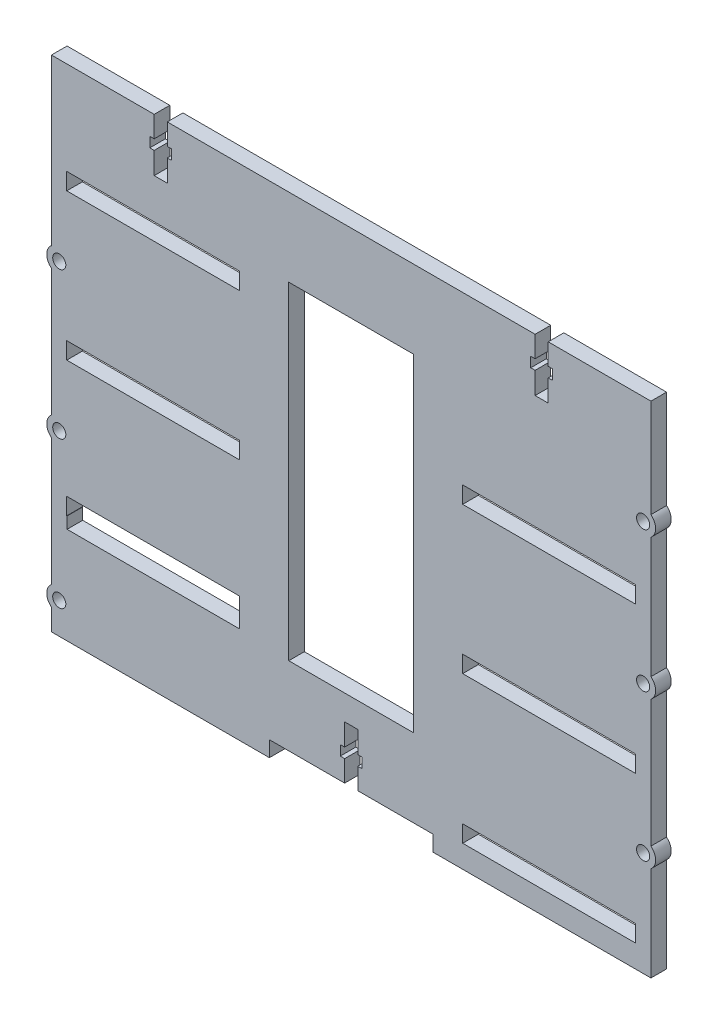
SolidWorks part; units mm, degrees
ref_plane "Front Plane" through (0, 0, 0) normal (0, 0, 1) x (1, 0, 0)
ref_plane "Top Plane" through (0, 0, 0) normal (0, 1, 0) x (1, 0, 0)
ref_plane "Right Plane" through (0, 0, 0) normal (1, 0, 0) x (0, 0, -1)
sketch "Sketch1" plane through (0, 0, 0) normal (0, 0, 1) x (1, 0, 0)
  line L0 (-192, 100.8775) -> (-192, 60.1225)
  line L1 (-192, 160) -> (-159.1, 160)
  line L2 (-192, 160) -> (-192, 107.1225)
  line L3 (-192, 0) -> (-122, 0)
  line L4 (0, 160) -> (0, 128.5225)
  line L5 (-187, 130) -> (-131.8, 130)
  line L6 (-187, 130) -> (-187, 124.95)
  line L7 (-187, 124.95) -> (-131.8, 124.95)
  line L8 (-131.8, 130) -> (-131.8, 124.95)
  line L9 (-192, 53.8775) -> (-192, 13.1225)
  line L10 (-187, 83) -> (-131.8, 83)
  line L11 (-187, 83) -> (-187, 77.95)
  line L12 (-187, 77.95) -> (-131.8, 77.95)
  line L13 (-131.8, 83) -> (-131.8, 77.95)
  line L14 (-192, 6.8775) -> (-192, 0)
  line L15 (-187, 36) -> (-131.8, 36)
  line L16 (-187, 36) -> (-187, 30.95)
  line L17 (-187, 30.95) -> (-131.8, 30.95)
  line L18 (-131.8, 36) -> (-131.8, 30.95)
  line L19 (0, 122.2775) -> (0, 83.5725)
  line L20 (0, 77.3275) -> (0, 36.5725)
  line L21 (-5, 101.4) -> (-60.2, 101.4)
  line L22 (-5, 101.4) -> (-5, 106.45)
  line L23 (-5, 106.45) -> (-60.2, 106.45)
  line L24 (-60.2, 101.4) -> (-60.2, 106.45)
  line L25 (0, 30.3275) -> (0, 0)
  line L26 (-5, 54.4) -> (-60.2, 54.4)
  line L27 (-5, 54.4) -> (-5, 59.45)
  line L28 (-5, 59.45) -> (-60.2, 59.45)
  line L29 (-60.2, 54.4) -> (-60.2, 59.45)
  line L30 (-159.1, 160) -> (-159.1, 153.2)
  line L31 (-5, 7.4) -> (-60.2, 7.4)
  line L32 (-5, 7.4) -> (-5, 12.45)
  line L33 (-5, 12.45) -> (-60.2, 12.45)
  line L34 (-60.2, 7.4) -> (-60.2, 12.45)
  line L35 (-159.1, 153.2) -> (-160.5, 153.2)
  line L36 (-160.5, 153.2) -> (-160.5, 150)
  line L37 (-160.5, 150) -> (-159.1, 150)
  line L38 (-159.1, 150) -> (-159.1, 143)
  line L39 (-159.1, 143) -> (-154.9, 143)
  line L40 (-154.9, 143) -> (-154.9, 150)
  line L41 (-154.9, 150) -> (-153.5, 150)
  line L42 (-153.5, 150) -> (-153.5, 153.2)
  line L43 (-153.5, 153.2) -> (-154.9, 153.2)
  line L44 (-154.9, 153.2) -> (-154.9, 160)
  line L45 (-32.9, 153.2) -> (-32.9, 160)
  line L46 (-31.5, 153.2) -> (-32.9, 153.2)
  line L47 (-31.5, 150) -> (-31.5, 153.2)
  line L48 (-32.9, 150) -> (-31.5, 150)
  line L49 (-32.9, 143) -> (-32.9, 150)
  line L50 (-37.1, 143) -> (-32.9, 143)
  line L51 (-37.1, 150) -> (-37.1, 143)
  line L52 (-38.5, 150) -> (-37.1, 150)
  line L53 (-38.5, 153.2) -> (-38.5, 150)
  line L54 (-37.1, 153.2) -> (-38.5, 153.2)
  line L55 (-37.1, 160) -> (-37.1, 153.2)
  line L58 (-192, 80) -> (0, 80) construction
  line L83 (-70, 0) -> (0, 0)
  line L85 (-122, 0) -> (-122, 5)
  line L86 (-122, 5) -> (-98.1, 5)
  line L87 (-70, 0) -> (-70, 5)
  line L88 (-32.9, 160) -> (0, 160)
  line L89 (-154.9, 160) -> (-37.1, 160)
  line L90 (-96, 5) -> (-96, 30.3525) construction
  line L91 (-93.9, 22) -> (-98.1, 22)
  line L92 (-98.1, 22) -> (-98.1, 15)
  line L93 (-98.1, 15) -> (-99.5, 15)
  line L94 (-99.5, 11.8) -> (-98.1, 11.8)
  line L95 (-98.1, 11.8) -> (-98.1, 5)
  line L96 (-99.5, 15) -> (-99.5, 11.8)
  line L98 (-92.5, 15) -> (-92.5, 11.8)
  line L99 (-93.9, 11.8) -> (-93.9, 5)
  line L100 (-92.5, 11.8) -> (-93.9, 11.8)
  line L101 (-93.9, 15) -> (-92.5, 15)
  line L102 (-93.9, 22) -> (-93.9, 15)
  line L103 (-93.9, 5) -> (-70, 5)
  circle A0 centre (-189.5, 104) radius 2.1
  arc A1 (-192, 107.1225) -> (-192, 100.8775) centre (-189.5, 104) ccw
  circle A2 centre (-189.5, 57) radius 2.1
  arc A3 (-192, 60.1225) -> (-192, 53.8775) centre (-189.5, 57) ccw
  circle A4 centre (-189.5, 10) radius 2.1
  arc A5 (-192, 13.1225) -> (-192, 6.8775) centre (-189.5, 10) ccw
  circle A6 centre (-2.5, 125.4) radius 2.1
  arc A7 (0, 122.2775) -> (0, 128.5225) centre (-2.5, 125.4) ccw
  circle A8 centre (-2.5, 80.45) radius 2.1
  arc A9 (0, 77.3275) -> (0, 83.5725) centre (-2.5, 80.45) ccw
  circle A10 centre (-2.5, 33.45) radius 2.1
  arc A11 (0, 30.3275) -> (0, 36.5725) centre (-2.5, 33.45) ccw
  point P68 (-157, 143)
  point P81 (-70, 2.5)
  point P82 (-35, 143)
  point P98 (-96, 22)
  dimension "D6" = 4.2
  dimension "D7" = 20.95
  dimension "D8" = 2.5
  dimension "D9" = 5.05
  dimension "D13" = 4
  dimension "D14" = 4.2
  dimension "D15" = 2.5
  dimension "D17" = 4
  dimension "D21" = 4.2
  dimension "D22" = 2.5
  dimension "D24" = 4
  dimension "D25" = 4.2
  dimension "D26" = 2.5
  dimension "D27" = 5.05
  dimension "D31" = 4.2
  dimension "D32" = 2.5
  dimension "D33" = 20.95
  dimension "D34" = 5.05
  dimension "D35" = 21
  dimension "D36" = 4.2
  dimension "D37" = 2.5
  dimension "D38" = 20.95
  dimension "D39" = 4
  dimension "D40" = 21
  dimension "D42" = 4
  dimension "D43" = 4
  dimension "D65" = 34.6
  dimension "D1" = 192
  dimension "D2" = 160
  dimension "D3" = 55.2
  dimension "D4" = 5
  dimension "D5" = 30
  dimension "D10" = 5.05
  dimension "D11" = 21
  dimension "D12" = 5
  dimension "D16" = 20.95
  dimension "D18" = 5.05
  dimension "D19" = 21
  dimension "D20" = 5
  dimension "D23" = 20.95
  dimension "D28" = 18.5
  dimension "D29" = 5
  dimension "D30" = 55.2
  dimension "D41" = 5.05
  dimension "D44" = 7
  dimension "D45" = 4.2
  dimension "D46" = 4.2
  dimension "D47" = 6.8
  dimension "D48" = 3.2
  dimension "D49" = 17
  dimension "D50" = 1.4
  dimension "D51" = 3.2
  dimension "D52" = 35
  dimension "D54" = 5
  dimension "D55" = 70
  dimension "D56" = 70
  dimension "D57" = 35
  dimension "D58" = 122
  dimension "D59" = 2.1
  dimension "D60" = 3.5
  dimension "D61" = 17
  dimension "D62" = 6.8
  dimension "D63" = 3.2
  dimension "D64" = 26
  dimension "D53" = 2
extrude "Boss-Extrude1" add sketch "Sketch1" along normal blind 5
sketch "Sketch2" plane through (0, 0, 5) normal (0, 0, 1) x (1, 0, 0)
  line L0 (-187, 130) -> (-187, 124.95) construction
  line L1 (-187.1, 130.175) -> (-131.7, 130.175)
  line L2 (-187.1, 130.175) -> (-187.1, 124.775)
  line L3 (-187.1, 124.775) -> (-131.7, 124.775)
  line L4 (-131.7, 130.175) -> (-131.7, 124.775)
  line L5 (-131.7, 124.775) -> (-60.2, 124.775) construction
  line L7 (-187.4, 104) -> (-163.5896, 104) construction
  line L8 (-188.6868, 58.9362) -> (-172.7381, 58.9362) construction
  line L9 (-60.3, 106.625) -> (-4.9, 106.625)
  line L10 (-131.7, 77.825) -> (-131.7, 83.225)
  line L11 (-187.1, 83.225) -> (-131.7, 83.225)
  line L12 (-187.1, 77.825) -> (-187.1, 83.225)
  line L13 (-187.1, 77.825) -> (-131.7, 77.825)
  line L14 (-187.1, 40.0473) -> (-131.7, 40.0473)
  line L15 (-187.1, 40.0473) -> (-187.1, 34.6473)
  line L16 (-187.1, 34.6473) -> (-131.7, 34.6473)
  line L17 (-131.7, 40.0473) -> (-131.7, 34.6473)
  line L18 (-60.3, 106.625) -> (-60.3, 101.225)
  line L28 (-60.3, 101.225) -> (-4.9, 101.225)
  line L29 (-4.9, 106.625) -> (-4.9, 101.225)
  line L30 (-60.2, 106.45) -> (-60.2, 101.4) construction
  line L31 (-2.5, 80.45) -> (-40.0415, 80.45) construction
  line L32 (-4.9, 54.275) -> (-4.9, 59.675)
  line L33 (-60.3, 59.675) -> (-4.9, 59.675)
  line L34 (-60.3, 54.275) -> (-60.3, 59.675)
  line L35 (-60.3, 54.275) -> (-4.9, 54.275)
  line L36 (-2.5, 33.45) -> (-34.1533, 33.45) construction
  line L37 (-60.3, 12.625) -> (-4.9, 12.625)
  line L38 (-60.3, 12.625) -> (-60.3, 7.225)
  line L39 (-60.3, 7.225) -> (-4.9, 7.225)
  line L40 (-4.9, 12.625) -> (-4.9, 7.225)
  circle A0 centre (-189.5, 104) radius 2.1 construction
  circle A1 centre (-189.5, 57) radius 2.1 construction
  point P6 (-187, 127.475)
  point P30 (-60.2, 103.925)
  dimension "D5" = 55.4
  dimension "D1" = 55.4
  dimension "D2" = 0.1
  dimension "D3" = 5.4
  dimension "D4" = 2.7
  dimension "D6" = 0.1
  dimension "D7" = 5.4
  dimension "D8" = 2.7
extrude "Cut-Extrude1" cut sketch "Sketch2" against normal blind 10
sketch "Sketch3" plane through (0, 0, 5) normal (0, 0, 1) x (1, 0, 0)
  line L0 (-192, 0) -> (-122, 0) construction
  line L1 (-122.2, 0) -> (-69.8, 0)
  line L2 (-122.2, 0) -> (-122.2, 5)
  line L3 (-122.2, 5) -> (-69.8, 5)
  line L4 (-69.8, 0) -> (-69.8, 5)
  line L6 (-122, 0) -> (-122, 5) construction
  dimension "D1" = 5
  dimension "D2" = 52.4
  dimension "D3" = 0.2
extrude "Cut-Extrude2" cut sketch "Sketch3" against normal blind 10
sketch "Sketch4" plane through (0, 0, 5) normal (0, 0, 1) x (1, 0, 0)
  line L0 (-37.1, 160) -> (-154.9, 160) construction
  line L1 (-116, 135) -> (-76, 135)
  line L2 (-116, 135) -> (-116, 30)
  line L3 (-116, 30) -> (-76, 30)
  line L4 (-76, 135) -> (-76, 30)
  line L5 (-122.2, 5) -> (-98.1, 5) construction
  point P8 (-96, 160)
  point P9 (-96, 135)
  dimension "D1" = 25
  dimension "D2" = 25
  dimension "D3" = 40
extrude "Cut-Extrude3" cut sketch "Sketch4" against normal blind 10
